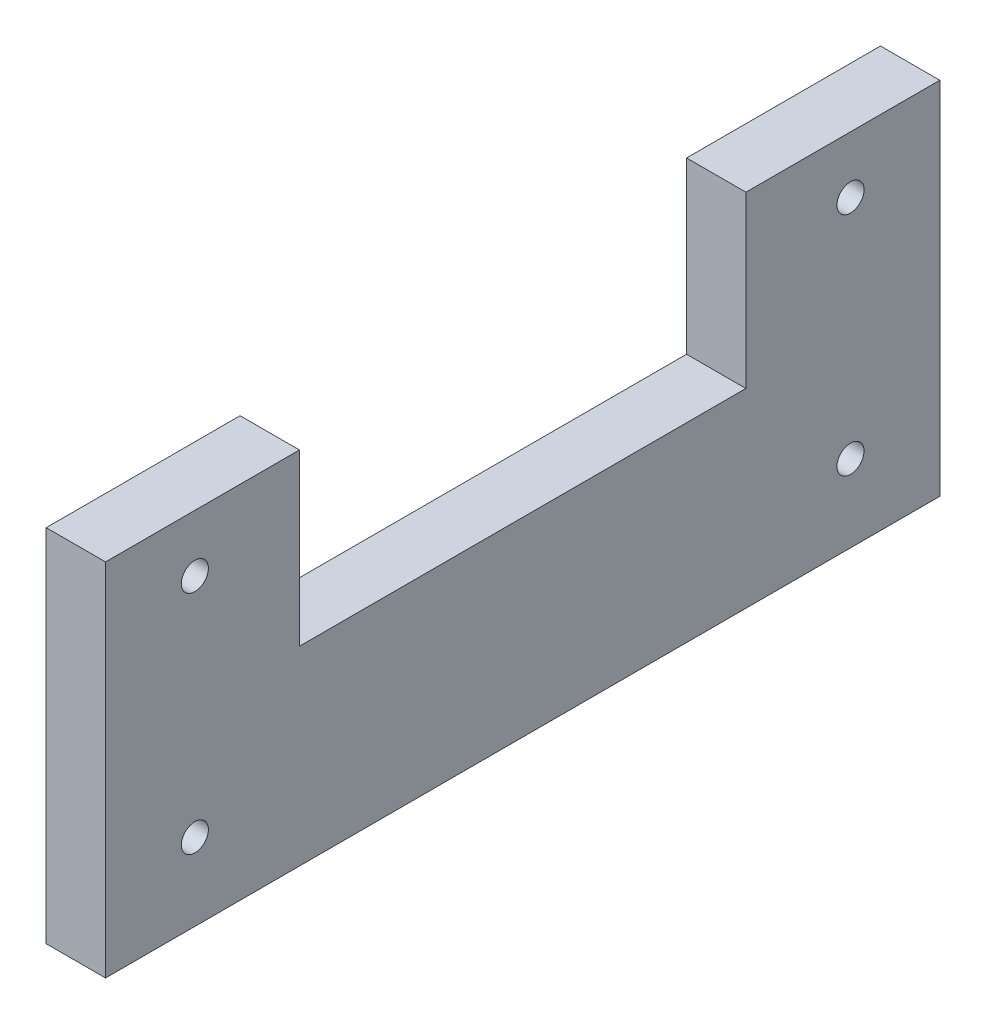
SolidWorks part; units mm, degrees
ref_plane "Front Plane" through (0, 0, 0) normal (0, 0, 1) x (1, 0, 0)
ref_plane "Top Plane" through (0, 0, 0) normal (0, 1, 0) x (1, 0, 0)
ref_plane "Right Plane" through (0, 0, 0) normal (1, 0, 0) x (0, 0, -1)
sketch "Sketch1" plane through (0, 0, 0) normal (1, 0, 0) x (0, 0, -1)
  line L1 (0, 0) -> (41.5073, 0)
  line L2 (0, 0) -> (0, 36.3876)
  line L3 (0, 36.3876) -> (41.5073, 36.3876)
  line L4 (41.5073, 0) -> (41.5073, 36.3876)
  line L5 (0, 0) -> (89.2964, 0)
  line L6 (0, 0) -> (0, -40.7542)
  line L7 (0, -40.7542) -> (89.2964, -40.7542)
  line L8 (89.2964, 0) -> (89.2964, -40.7542)
extrude "Boss-Extrude1" add sketch "Sketch1" along normal blind 12.7 contours L1 L4 L3 L2 | L8 L5 L1 L6 L7
sketch "Sketch2" plane through (12.7, 0, 0) normal (1, 0, 0) x (0, 0, -1)
  circle A0 centre (19.1202, 24.225) radius 2.8997
extrude "Cut-Extrude1" cut sketch "Sketch2" against normal through all
mirror "Mirror1" about plane through (0, 0, 0) normal (0, 1, 0) of "Cut-Extrude1"
mirror "Mirror2" about plane through (12.7, 0, -89.2964) normal (0, 0, -1) of bodies 103
